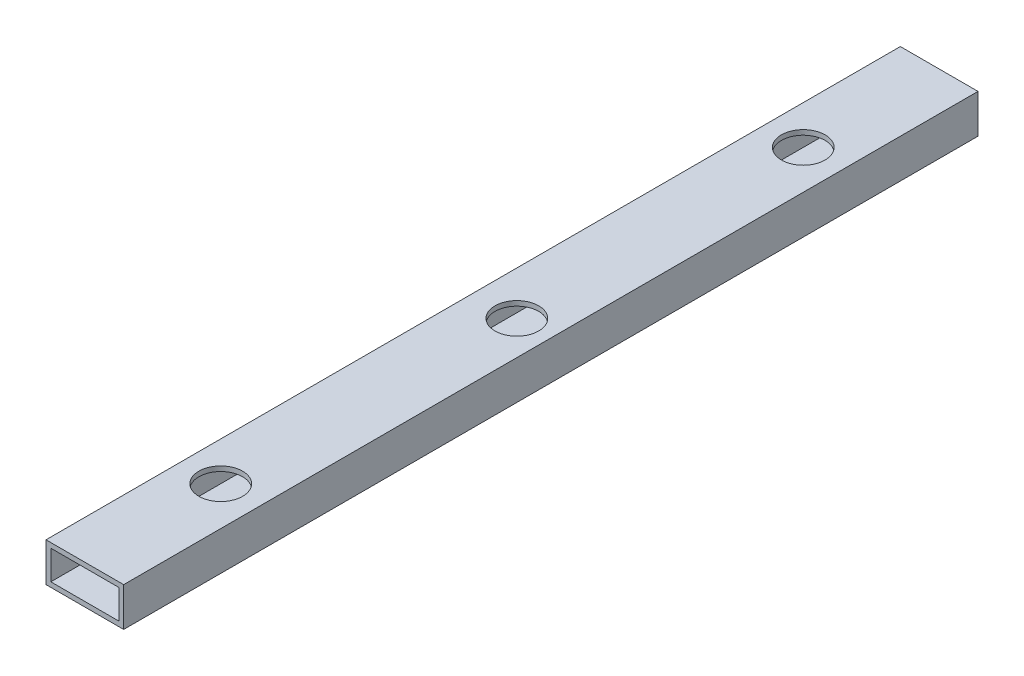
SolidWorks part; units mm, degrees
material "6061 Alloy"
ref_plane "Front Plane" through (0, 0, 0) normal (0, 0, 1) x (1, 0, 0)
ref_plane "Top Plane" through (0, 0, 0) normal (0, 1, 0) x (1, 0, 0)
ref_plane "Right Plane" through (0, 0, 0) normal (1, 0, 0) x (0, 0, -1)
sketch "Sketch1" plane through (0, 0, 0) normal (0, 0, 1) x (1, 0, 0)
  line L0 (3.175, 22.225) -> (47.625, 22.225)
  line L1 (0, 0) -> (50.8, 0)
  line L2 (0, 0) -> (0, 25.4)
  line L3 (0, 25.4) -> (50.8, 25.4)
  line L4 (50.8, 0) -> (50.8, 25.4)
  line L5 (47.625, 3.175) -> (47.625, 22.225)
  line L6 (3.175, 3.175) -> (47.625, 3.175)
  line L7 (3.175, 3.175) -> (3.175, 22.225)
  dimension "D1" = 50.8
  dimension "D2" = 25.4
  dimension "D3" = 3.175
extrude "Boss-Extrude1" add sketch "Sketch1" along normal blind 558.8
sketch "Sketch2" plane through (0, 25.4, 0) normal (0, 1, 0) x (1, 0, 0)
  line L0 (25.4, 0) -> (25.4, -558.8) construction
  line L1 (50.8, 0) -> (0, 0) construction
  line L2 (50.8, -558.8) -> (0, -558.8) construction
  line L3 (0, -279.4) -> (50.8, -279.4) construction
  line L4 (0, -558.8) -> (0, 0) construction
  line L5 (50.8, -558.8) -> (50.8, 0) construction
  circle A0 centre (28.575, -279.4) radius 14.2875
  circle A1 centre (25.4, -469.9) radius 14.2875
  circle A2 centre (25.4, -88.9) radius 14.2875
  dimension "D1" = 28.575
  dimension "D3" = 28.575
  dimension "D2" = 88.9
  dimension "D4" = 3.175
extrude "Cut-Extrude1" cut sketch "Sketch2" against normal through all
